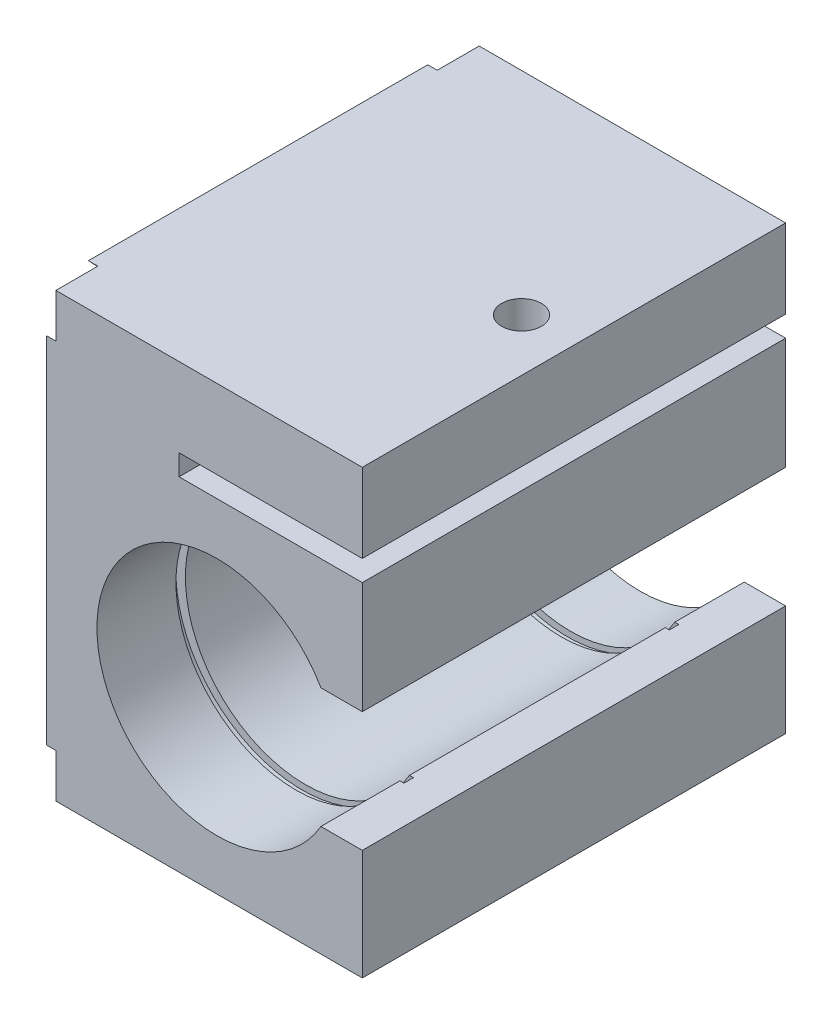
SolidWorks part; units mm, degrees
material "AISI 1020"
ref_plane "Front Plane" through (0, 0, 0) normal (0, 0, 1) x (1, 0, 0)
ref_plane "Top Plane" through (0, 0, 0) normal (0, 1, 0) x (1, 0, 0)
ref_plane "Right Plane" through (0, 0, 0) normal (1, 0, 0) x (0, 0, -1)
sketch "Esquisse1" plane through (0, 0, 0) normal (0, 0, 1) x (1, 0, 0)
  line L0 (50, 57.5) -> (0, 57.5) construction
  line L1 (0, 0) -> (50, 0)
  line L2 (0, 0) -> (0, 70)
  line L3 (0, 70) -> (50, 70)
  line L4 (50, 0) -> (50, 17.5)
  line L5 (50, 57.5) -> (50, 70)
  line L6 (50, 57.5) -> (21, 57.5)
  line L8 (50, 54.2) -> (21, 54.2)
  line L9 (21, 57.5) -> (21, 54.2)
  line L14 (50, 36.5) -> (43.4545, 36.5)
  line L15 (43.4545, 17.5) -> (50, 17.5)
  line L18 (27, 27) -> (50, 27) construction
  line L19 (50, 36.5) -> (50, 54.2)
  arc A0 (43.4545, 36.5) -> (43.4545, 17.5) centre (27, 27) ccw
  dimension "D8" = 38
  dimension "D1" = 50
  dimension "D2" = 70
  dimension "D3" = 12.5
  dimension "D4" = 29
  dimension "D5" = 3.3
  dimension "D6" = 27
  dimension "D7" = 27
  dimension "D9" = 19
extrude "Boss.-Extru.1" add sketch "Esquisse1" along normal blind 67
sketch "Esquisse2" plane through (0, 70, 0) normal (0, 1, 0) x (1, 0, 0)
  line L0 (-27.5, 0) -> (27.5, 0) construction
  line L1 (50, -67) -> (50, 0) construction
  circle A0 centre (41.7, -33.5) radius 3.15
  dimension "D3" = 6.3
  dimension "D1" = 33.5
  dimension "D2" = 8.3
extrude "Enlèv. mat.-Extru.1" cut sketch "Esquisse2" against normal up to next
sketch "Esquisse8" plane through (0, 0, 0) normal (-1, 0, 0) x (0, 0, 1)
  line L0 (0, 70) -> (67, 0) construction
  line L1 (0, -27.5) -> (0, 27.5) construction
  line L2 (67, 70) -> (0, 70) construction
  line L3 (67, 70) -> (0, 0) construction
  line L4 (63.5324, 73.319) -> (33.5, 41.9419)
  line L5 (63.5324, 73.319) -> (70.4676, 66.681)
  line L6 (-3.4676, 3.319) -> (3.4676, -3.319)
  line L7 (70.4676, 66.681) -> (40.1444, 35)
  line L8 (63.5324, 73.319) -> (3.4676, -3.319) construction
  line L9 (-3.4676, 3.319) -> (70.4676, 66.681) construction
  line L10 (67, 70) -> (0, 0) construction
  line L11 (-3.4676, 66.681) -> (26.8556, 35)
  line L12 (-3.4676, 66.681) -> (3.4676, 73.319)
  line L13 (63.5324, -3.319) -> (70.4676, 3.319)
  line L14 (3.4676, 73.319) -> (33.5, 41.9419)
  line L15 (-3.4676, 66.681) -> (70.4676, 3.319) construction
  line L16 (63.5324, -3.319) -> (3.4676, 73.319) construction
  line L17 (0, 70) -> (67, 0) construction
  line L18 (26.8556, 35) -> (-3.4676, 3.319)
  line L19 (33.5, 28.0581) -> (3.4676, -3.319)
  line L20 (40.1444, 35) -> (70.4676, 3.319)
  line L21 (33.5, 28.0581) -> (63.5324, -3.319)
  point P11 (33.5, 35)
  point P12 (33.5, 35)
  dimension "D1" = 9.6
  dimension "D2" = 9.6
extrude "Enlèv. mat.-Extru.3" cut sketch "Esquisse8" against normal blind 1.5
ref_plane "Plan1" through (0, 27, 0) normal (0, 1, 0) x (1, 0, 0)
ref_plane "Plan3" through (0, 0, 67) normal (0, 0, 1) x (1, 0, 0)
sketch "Esquisse10" plane through (0, 0, 67) normal (0, 0, 1) x (1, 0, 0)
  line L0 (27, 46) -> (27, 8) construction
  line L1 (8, 27) -> (52.4868, 27) construction
  line L2 (3.6, 27) -> (-3.6, 27) construction
  arc A0 (43.4545, 36.5) -> (43.4545, 17.5) centre (27, 27) ccw construction
sketch "Esquisse12" plane through (0, 27, 0) normal (0, 1, 0) x (1, 0, 0)
  line L0 (26.4914, -66.2363) -> (26.4914, -4.2363) construction
  line L1 (8, -67) -> (52.4868, -67) construction
  line L3 (41.6489, -53) -> (46.4914, -53)
  line L4 (41.6489, -53) -> (41.6489, -54.5)
  line L5 (41.6489, -54.5) -> (46.4914, -54.5)
  line L6 (46.4914, -53) -> (46.4914, -54.5)
  dimension "D1" = 20
  dimension "D2" = 1.5
  dimension "D3" = 12.5
revolve "Enlèvement de matière-Révolution2" cut sketch "Esquisse12" angle 360 about L0
pattern_linear "Répétition linéaire1" count 2 spacing 42 along (0, 0, -1) of "Enlèvement de matière-Révolution2"
